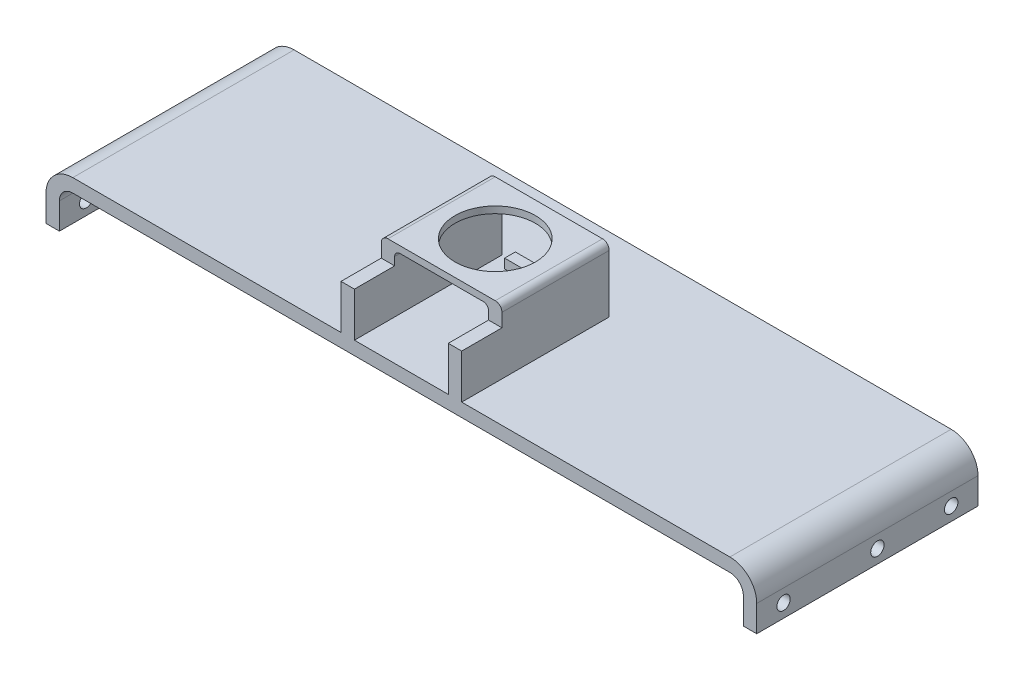
SolidWorks part; units mm, degrees
ref_plane "Front Plane" through (0, 0, 0) normal (0, 0, 1) x (1, 0, 0)
ref_plane "Top Plane" through (0, 0, 0) normal (0, 1, 0) x (1, 0, 0)
ref_plane "Right Plane" through (0, 0, 0) normal (1, 0, 0) x (0, 0, -1)
sketch "Sketch1" plane through (0, 0, 0) normal (0, 0, 1) x (1, 0, 0)
  line L0 (0, 0) -> (0, 19.6)
  line L3 (0, 19.6) -> (20, 19.6) construction
  line L4 (20, 19.6) -> (20, 39.6) construction
  line L5 (0, 0) -> (10, 0)
  line L6 (265, 0) -> (265, 41.1401) construction
  line L7 (20, 39.6) -> (510, 39.6)
  line L8 (530, 0) -> (530, 19.6)
  line L9 (0, 0) -> (10, 0)
  line L10 (20, 29.6) -> (510, 29.6)
  line L12 (10, 19.6) -> (10, 0)
  line L13 (520, 19.6) -> (520, 0)
  line L14 (520, 0) -> (530, 0)
  arc A2 (20, 39.6) -> (0, 19.6) centre (20, 19.6) ccw
  arc A3 (510, 39.6) -> (530, 19.6) centre (510, 19.6) cw
  arc A4 (20, 29.6) -> (10, 19.6) centre (20, 19.6) ccw
  arc A5 (510, 29.6) -> (520, 19.6) centre (510, 19.6) cw
  point P15 (265, 39.6)
  point P19 (265, 29.6)
  dimension "D1" = 19.6
  dimension "D2" = 20
  dimension "D4" = 530
extrude "Boss-Extrude2" add sketch "Sketch1" along normal blind 165 contours L10 A5 L13 L14 L8 A3 L7 A2 L0 L5 L12 A4
sketch "Sketch2" plane through (0, 0, 0) normal (-1, 0, 0) x (0, 0, 1)
  line L0 (165, 0) -> (0, 0) construction
  line L1 (0, 0) -> (0, 19.6) construction
  line L2 (82.5, 0) -> (82.5, 42.8019) construction
  circle A0 centre (20, 10) radius 5
  circle A1 centre (145, 10) radius 5
  circle A3 centre (75, 10) radius 5
  dimension "D1" = 10
  dimension "D2" = 10
  dimension "D3" = 20
  dimension "D5" = 2
extrude "Cut-Extrude1" cut sketch "Sketch2" against normal through all
sketch "Sketch3" plane through (0, 39.6, 0) normal (0, 1, 0) x (1, 0, 0)
  line L0 (265, -165) -> (265, -104.5686)
  line L1 (20, -165) -> (510, -165) construction
  line L2 (265, -165) -> (230, -165)
  line L3 (265, -165) -> (300, -165)
  line L4 (230, -165) -> (230, -55)
  line L5 (300, -165) -> (300, -55)
  line L6 (230, -55) -> (220, -55)
  line L7 (220, -55) -> (220, -165)
  line L8 (300, -55) -> (310, -55)
  line L9 (310, -55) -> (310, -165)
  line L10 (220, -165) -> (230, -165)
  line L11 (300, -165) -> (310, -165)
  line M9 (20, -165) -> (510, -165)
  dimension "D1" = 45
  dimension "D2" = 45
  dimension "D3" = 10
  dimension "D4" = 110
  dimension "D5" = 10
  dimension "D6" = 110
extrude "Boss-Extrude3" add sketch "Sketch3" along normal blind 33 contours L6 L7 L4 M9 | L5 L8 L9 L11
sketch "Sketch4" plane through (0, 0, 55) normal (0, 0, -1) x (-1, 0, 0)
  line L0 (-300, 72.6) -> (-300, 78.6)
  line L1 (-310, 72.6) -> (-310, 82.6)
  line L2 (-230, 72.6) -> (-230, 78.6)
  line L3 (-220, 72.6) -> (-220, 82.6)
  line L4 (-296, 82.6) -> (-234, 82.6)
  line L5 (-305, 87.6) -> (-225, 87.6)
  line L6 (-310, 72.6) -> (-300, 72.6)
  line L7 (-230, 72.6) -> (-220, 72.6)
  arc A0 (-220, 82.6) -> (-225, 87.6) centre (-225, 82.6) ccw
  arc A1 (-305, 87.6) -> (-310, 82.6) centre (-305, 82.6) ccw
  arc A2 (-230, 78.6) -> (-234, 82.6) centre (-234, 78.6) ccw
  arc A3 (-296, 82.6) -> (-300, 78.6) centre (-296, 78.6) ccw
  point P14 (-220, 87.6)
  point P17 (-310, 87.6)
  point P20 (-230, 82.6)
  point P23 (-300, 82.6)
  dimension "D5" = 5
  dimension "D6" = 4
  dimension "D1" = 10
  dimension "D2" = 15
  dimension "D3" = 10
  dimension "D4" = 15
extrude "Boss-Extrude4" add sketch "Sketch4" against normal blind 80
sketch "Sketch5" plane through (0, 87.6, 0) normal (0, 1, 0) x (1, 0, 0)
  line L0 (265, -55) -> (265, -95)
  line L1 (225, -55) -> (305, -55) construction
  circle A0 centre (265, -95) radius 30
  dimension "D1" = 40
extrude "Cut-Extrude2" cut sketch "Sketch5" along direction (0, 1, 0) on the side against the normal blind 5 contours A0
sketch3d "3DSketch2"
  line L0 (300, 39.6, 165) -> (300, 39.6, 55) construction
  line L1 (290, 39.6, 55) -> (240, 39.6, 55)
  line L2 (290, 39.6, 55) -> (290, 39.6, 60.3231)
  line L3 (240, 39.6, 55) -> (240, 39.6, 63)
  line L4 (240, 39.6, 63) -> (290, 39.6, 63)
  line L5 (290, 39.6, 60.3231) -> (290, 39.6, 63)
  line L6 (300, 39.6, 55) -> (310, 39.6, 55) construction
  dimension "D1" = 10
  dimension "D2" = 10
  dimension "D3" = 8
extrude "Boss-Extrude5" add sketch "3DSketch2" along direction (0, 1, 0) on the side against the normal blind 7 contours L1 L3 L4 L5 L2
